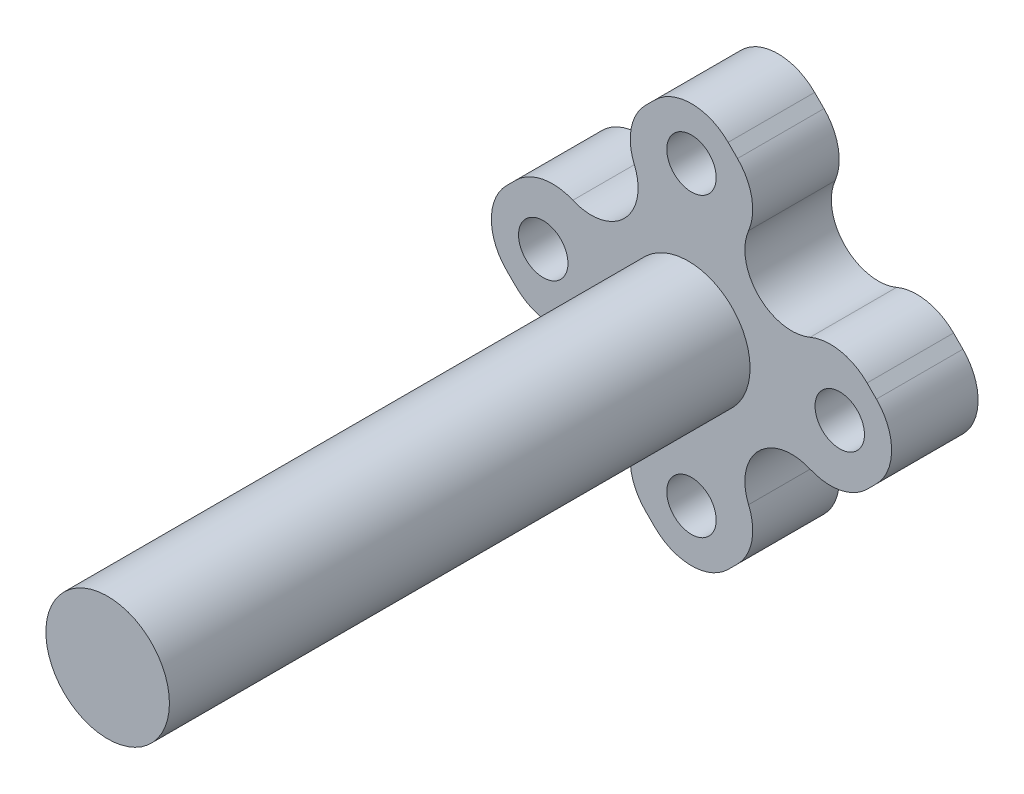
SolidWorks part; units mm, degrees
ref_plane "前视基准面" through (0, 0, 0) normal (0, 0, 1) x (1, 0, 0)
ref_plane "上视基准面" through (0, 0, 0) normal (0, 1, 0) x (1, 0, 0)
ref_plane "右视基准面" through (0, 0, 0) normal (1, 0, 0) x (0, 0, -1)
other "Configuration Table"
sketch "草图1" plane through (0, 0, 0) normal (0, 0, 1) x (1, 0, 0)
  line L0 (-1.734, 7.0892) -> (-1.3561, 7.4672)
  line L1 (1.6138, 7.4672) -> (1.9918, 7.0892)
  line L2 (-7.3561, 1.4672) -> (-6.9781, 1.8452)
  line L3 (-6.9781, -1.8806) -> (-7.3561, -1.5026)
  line L4 (-1.3561, -7.5026) -> (-1.734, -7.1247)
  line L5 (1.9918, -7.1247) -> (1.6138, -7.5026)
  line L6 (7.6138, -1.5026) -> (7.2358, -1.8806)
  line L7 (7.2358, 1.8452) -> (7.6138, 1.4672)
  arc A0 (-0.8711, 5.9823) -> (1.1289, 5.9823) centre (0.1289, 5.9823) ccw
  arc A1 (1.1289, 5.9823) -> (-0.8711, 5.9823) centre (0.1289, 5.9823) ccw
  arc A2 (1.6138, 7.4672) -> (-1.3561, 7.4672) centre (0.1289, 5.9823) ccw
  arc A3 (-1.734, 7.0892) -> (-2.1825, 4.7846) centre (-0.2491, 5.6043) ccw
  arc A4 (2.6068, 5.6043) -> (1.9918, 7.0892) centre (0.5068, 5.6043) ccw
  arc A5 (2.4402, 4.7846) -> (2.6068, 5.6043) centre (0.5068, 5.6043) ccw
  arc A6 (2.4402, 4.7846) -> (4.9312, 2.2937) centre (4.1895, 4.0429) ccw
  arc A7 (-4.6734, 2.2937) -> (-2.0318, 4.0429) centre (-3.9318, 4.0429) ccw
  arc A8 (-2.0318, 4.0429) -> (-2.1825, 4.7846) centre (-3.9318, 4.0429) ccw
  arc A9 (-4.6734, 2.2937) -> (-6.9781, 1.8452) centre (-5.4932, 0.3603) ccw
  arc A10 (-7.3561, 1.4672) -> (-7.3561, -1.5026) centre (-5.8711, -0.0177) ccw
  arc A11 (-6.9781, -1.8806) -> (-4.6734, -2.3291) centre (-5.4932, -0.3957) ccw
  arc A12 (-2.0318, -4.0784) -> (-4.6734, -2.3291) centre (-3.9318, -4.0784) ccw
  arc A13 (-2.1825, -4.82) -> (-2.0318, -4.0784) centre (-3.9318, -4.0784) ccw
  arc A14 (-2.1825, -4.82) -> (-1.734, -7.1247) centre (-0.2491, -5.6397) ccw
  arc A15 (-1.3561, -7.5026) -> (1.6138, -7.5026) centre (0.1289, -6.0177) ccw
  arc A16 (1.9918, -7.1247) -> (2.6068, -5.6397) centre (0.5068, -5.6397) ccw
  arc A17 (4.9312, -2.3291) -> (2.4402, -4.82) centre (4.1895, -4.0784) ccw
  arc A18 (2.6068, -5.6397) -> (2.4402, -4.82) centre (0.5068, -5.6397) ccw
  arc A19 (-0.8711, -6.0177) -> (1.1289, -6.0177) centre (0.1289, -6.0177) ccw
  arc A20 (1.1289, -6.0177) -> (-0.8711, -6.0177) centre (0.1289, -6.0177) ccw
  arc A21 (4.9312, -2.3291) -> (7.2358, -1.8806) centre (5.7509, -0.3957) ccw
  arc A22 (7.6138, -1.5026) -> (8.2289, -0.0177) centre (6.1289, -0.0177) ccw
  arc A23 (8.2289, -0.0177) -> (7.6138, 1.4672) centre (6.1289, -0.0177) ccw
  arc A24 (7.2358, 1.8452) -> (4.9312, 2.2937) centre (5.7509, 0.3603) ccw
  arc A25 (5.1289, -0.0177) -> (7.1289, -0.0177) centre (6.1289, -0.0177) ccw
  arc A26 (7.1289, -0.0177) -> (5.1289, -0.0177) centre (6.1289, -0.0177) ccw
  arc A27 (-6.8711, -0.0177) -> (-4.8711, -0.0177) centre (-5.8711, -0.0177) ccw
  arc A28 (-4.8711, -0.0177) -> (-6.8711, -0.0177) centre (-5.8711, -0.0177) ccw
extrude "凸台-拉伸1" add sketch "草图1" along normal blind 3.5
sketch "草图3" plane through (0, 0, 3.5) normal (0, 0, 1) x (1, 0, 0)
  circle A0 centre (0, 0) radius 2.5
extrude "凸台-拉伸2" add sketch "草图3" along normal blind 23.5
